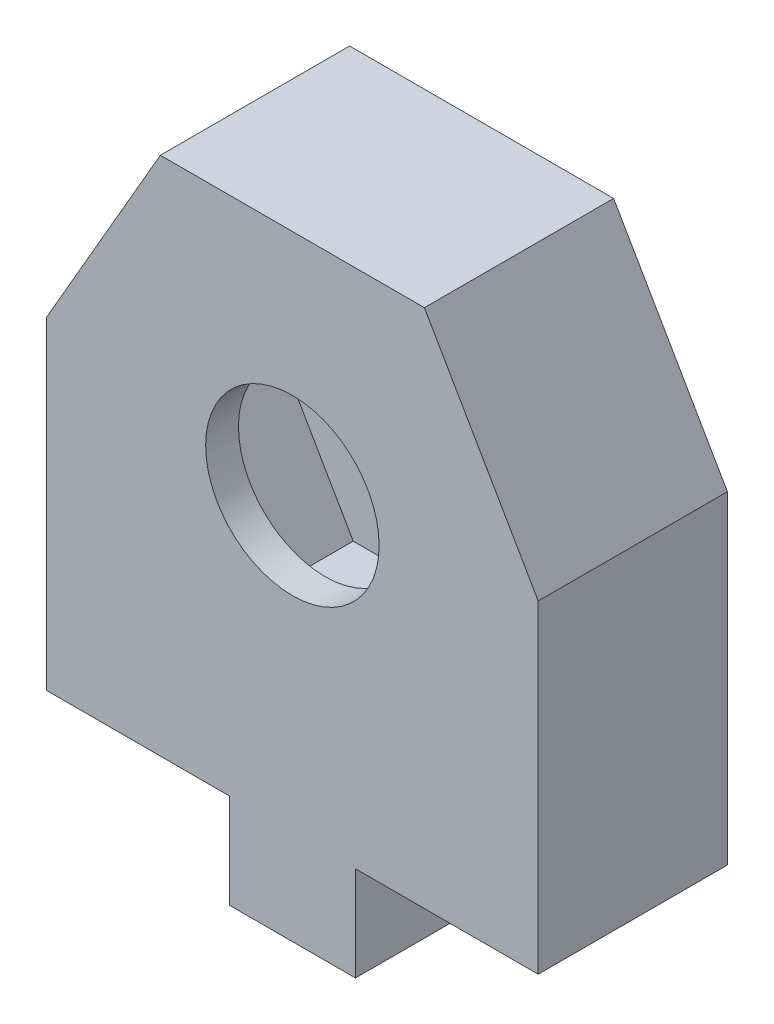
SolidWorks part; units mm, degrees
ref_plane "Front Plane" through (0, 0, 0) normal (0, 0, 1) x (1, 0, 0)
ref_plane "Top Plane" through (0, 0, 0) normal (0, 1, 0) x (1, 0, 0)
ref_plane "Right Plane" through (0, 0, 0) normal (1, 0, 0) x (0, 0, -1)
sketch "Sketch1" plane through (0, 0, 0) normal (0, 0, 1) x (1, 0, 0)
  line L0 (-1, -4.625) -> (-1, -6.125)
  line L2 (-3.8971, 0.5) -> (-3.8971, -4.625)
  line L3 (-3.8971, -4.625) -> (-1, -4.625)
  line L4 (3.8971, 0.5) -> (3.8971, -4.625)
  line L7 (3.0311, 0) -> (1.5155, 2.625) construction
  line L8 (1.5155, 2.625) -> (-1.5155, 2.625) construction
  line L9 (-1.5155, 2.625) -> (-3.0311, 0) construction
  line L10 (-3.0311, 0) -> (-1.5155, -2.625) construction
  line L11 (-1.5155, -2.625) -> (1.5155, -2.625) construction
  line L12 (1.5155, -2.625) -> (3.0311, 0) construction
  line L13 (-1, -6.125) -> (1, -6.125)
  line L14 (1, -6.125) -> (1, -4.625)
  line L15 (1, -4.625) -> (3.8971, -4.625)
  line L16 (3.8971, 0.5) -> (2.0929, 3.625)
  line L17 (2.0929, 3.625) -> (-2.0929, 3.625)
  line L18 (-2.0929, 3.625) -> (-3.8971, 0.5)
  circle A2 centre (0, 0) radius 2.625 construction
  circle A3 centre (0, 0) radius 1.375
  point P0 (0, 0)
  dimension "D3" = 1
  dimension "D7" = 2.75
  dimension "D2" = 2
  dimension "D4" = 5.25
  dimension "D5" = 2
  dimension "D6" = 1.5
extrude "Boss-Extrude1" add sketch "Sketch1" along normal blind 3
ref_plane "Plane1" through (0, 0, 1.5) normal (0, 0, 1) x (1, 0, 0)
sketch "Sketch2" plane through (0, 0, 1.5) normal (0, 0, 1) x (1, 0, 0)
  line L0 (-1.5155, -2.625) -> (1.5155, -2.625) construction
  line L1 (-3.0311, 0) -> (-1.5155, -2.625) construction
  line L2 (-1.5155, 2.625) -> (-3.0311, 0) construction
  line L3 (1.5155, 2.625) -> (-1.5155, 2.625) construction
  line L4 (1.5155, -2.625) -> (3.0311, 0) construction
  line L5 (3.0311, 0) -> (1.5155, 2.625) construction
  line L6 (-1.5155, -2.625) -> (1.5155, -2.625)
  line L7 (-3.0311, 0) -> (-1.5155, -2.625)
  line L8 (-1.5155, 2.625) -> (-3.0311, 0)
  line L9 (1.5155, 2.625) -> (-1.5155, 2.625)
  line L10 (1.5155, -2.625) -> (3.0311, 0)
  line L11 (3.0311, 0) -> (1.5155, 2.625)
extrude "Cut-Extrude1" cut sketch "Sketch2" against normal mid plane 1.96
